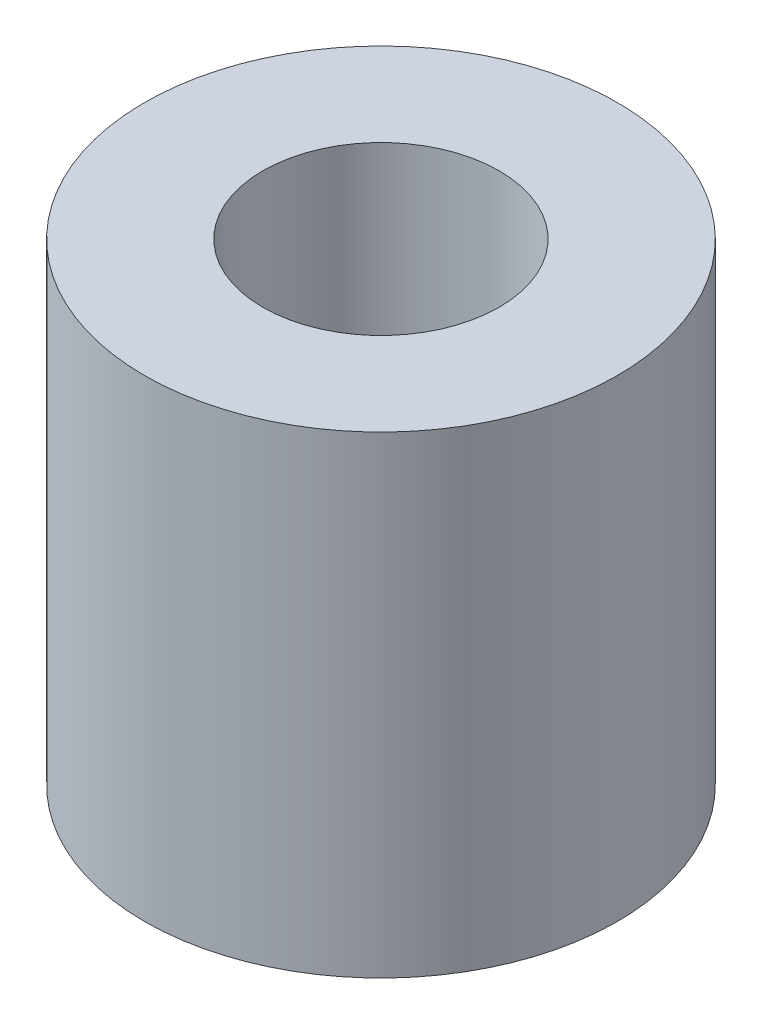
SolidWorks part; units mm, degrees
ref_plane "Front Plane" through (0, 0, 0) normal (0, 0, 1) x (1, 0, 0)
ref_plane "Top Plane" through (0, 0, 0) normal (0, 1, 0) x (1, 0, 0)
ref_plane "Right Plane" through (0, 0, 0) normal (1, 0, 0) x (0, 0, -1)
sketch "Sketch1" plane through (0, 0, 0) normal (0, 1, 0) x (1, 0, 0)
  circle A0 centre (0, 0) radius 1.27
  circle A1 centre (0, 0) radius 2.54
extrude "Boss-Extrude1" add sketch "Sketch1" along normal blind 5.08
